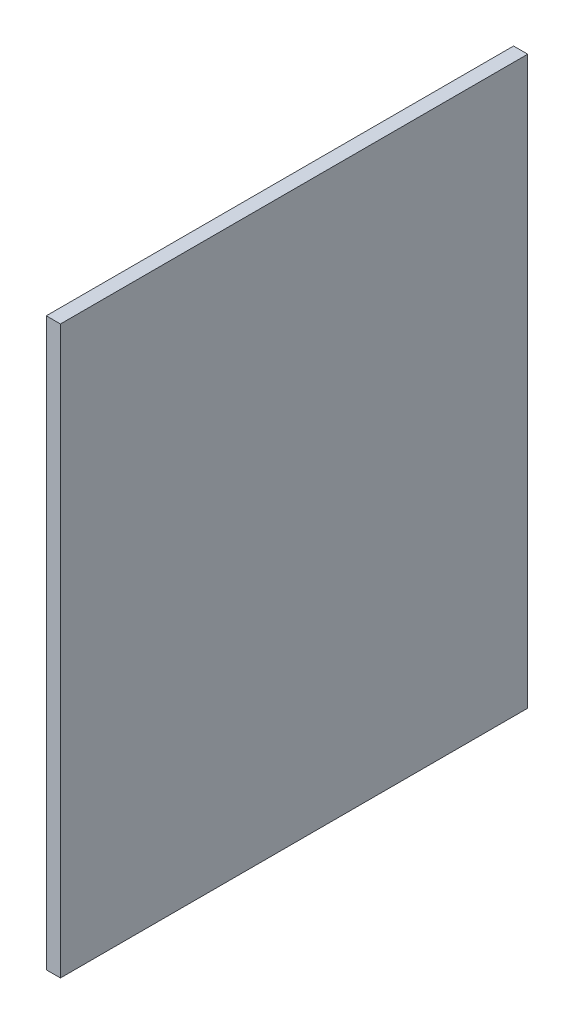
SolidWorks part; units mm, degrees
material "유리"
ref_plane "정면" through (0, 0, 0) normal (0, 0, 1) x (1, 0, 0)
ref_plane "윗면" through (0, 0, 0) normal (0, 1, 0) x (1, 0, 0)
ref_plane "우측면" through (0, 0, 0) normal (1, 0, 0) x (0, 0, -1)
sketch "스케치1" plane through (0, 0, 0) normal (1, 0, 0) x (0, 0, -1)
  line L1 (0, 0) -> (165, 0)
  line L2 (0, 0) -> (0, 200)
  line L3 (0, 200) -> (165, 200)
  line L4 (165, 0) -> (165, 200)
  dimension "D1" = 165
  dimension "D2" = 200
extrude "보스-돌출1" add sketch "스케치1" along normal blind 5
